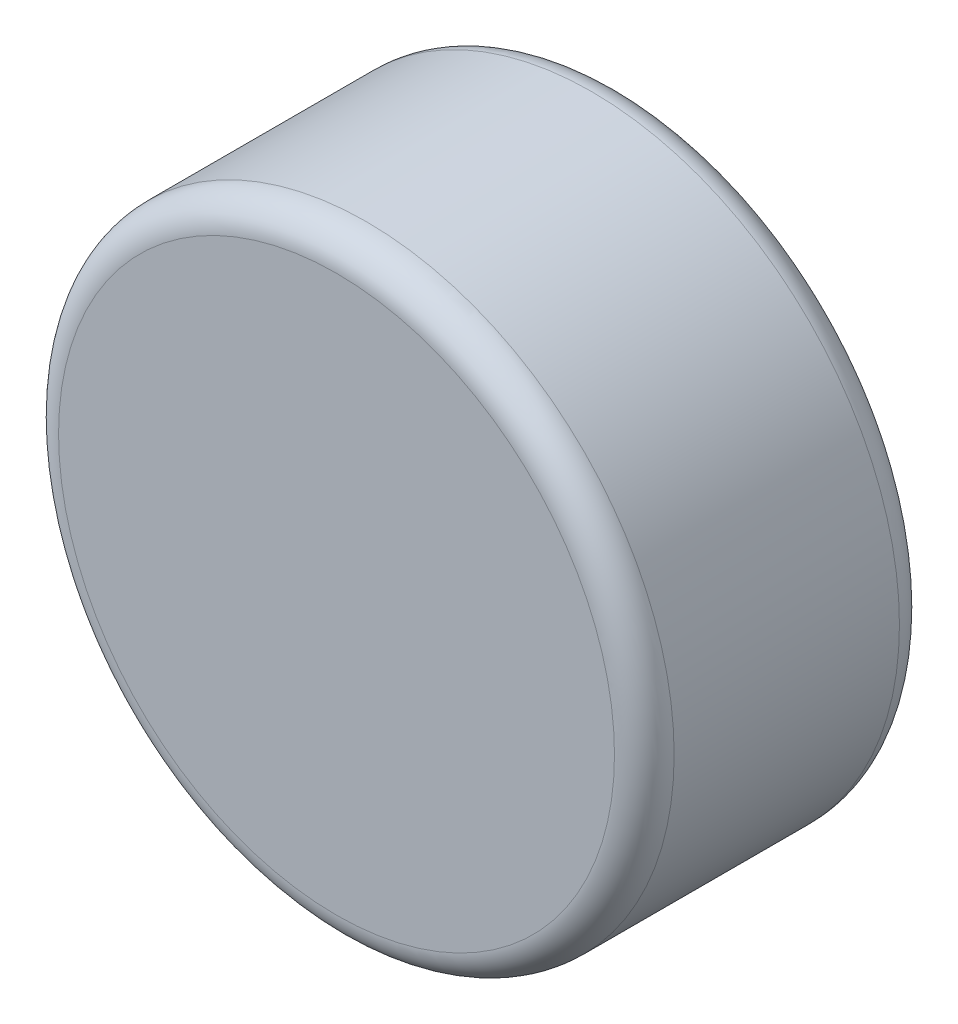
SolidWorks part; units mm, degrees
material "Rubber"
ref_plane "Front Plane" through (0, 0, 0) normal (0, 0, 1) x (1, 0, 0)
ref_plane "Top Plane" through (0, 0, 0) normal (0, 1, 0) x (1, 0, 0)
ref_plane "Right Plane" through (0, 0, 0) normal (1, 0, 0) x (0, 0, -1)
sketch "Sketch1" plane through (0, 0, 0) normal (0, 1, 0) x (1, 0, 0)
  line L0 (0, 0) -> (48.5, 0)
  line L1 (48.5, 0) -> (48.5, 44.9)
  line L2 (48.5, 44.9) -> (0, 44.9)
  line L5 (0, 44.9) -> (0, 0)
  line L6 (0, 0) -> (0, 52.8273) construction
  dimension "D2" = 44.9
  dimension "D4" = 48.5
revolve "Revolve1" add sketch "Sketch1" angle 360 about L6
sketch "Sketch2" plane through (0, 0, -44.9) normal (0, 0, -1) x (-1, 0, 0)
  circle A0 centre (0, 0) radius 4.125
  dimension "D1" = 8.25
extrude "Cut-Extrude1" cut sketch "Sketch2" against normal blind 26.4
fillet "Fillet1" radius 4.7 2 edges at (48.5, 0, 0) (48.5, 0, -44.9)
